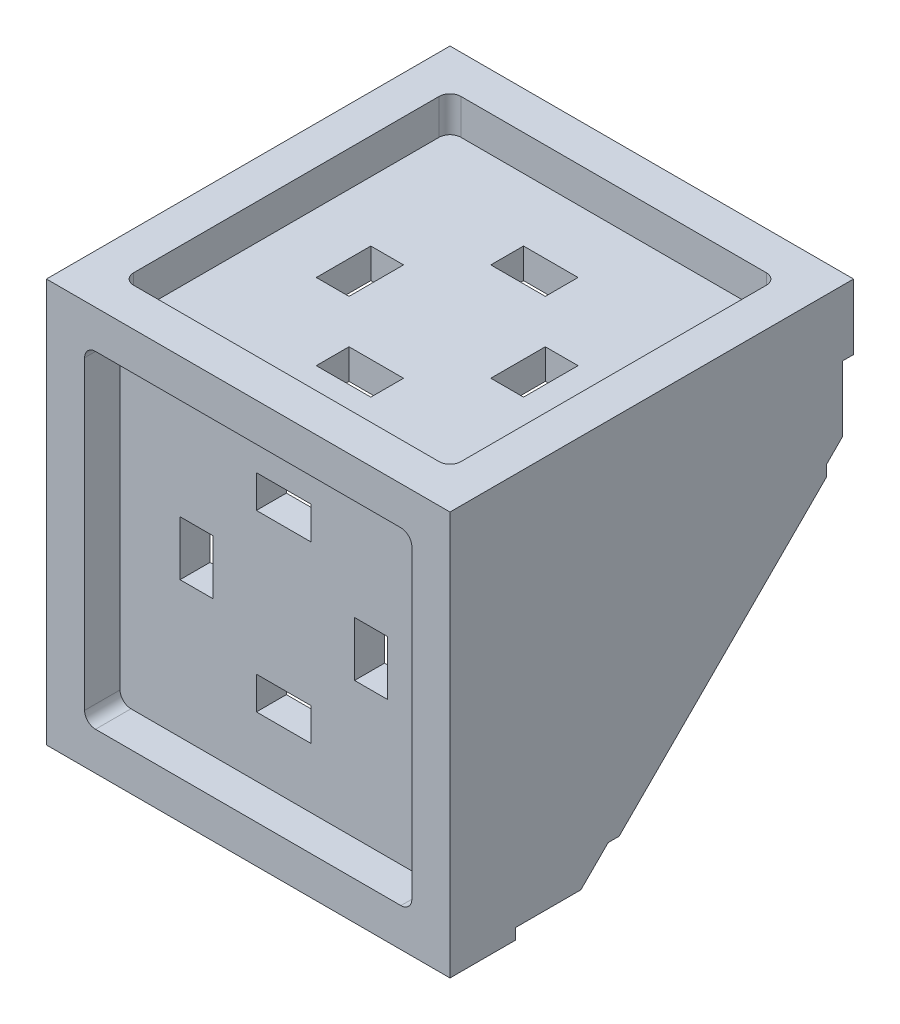
SolidWorks part; units mm, degrees
ref_plane "Front Plane" through (0, 0, 0) normal (0, 0, 1) x (1, 0, 0)
ref_plane "Top Plane" through (0, 0, 0) normal (0, 1, 0) x (1, 0, 0)
ref_plane "Right Plane" through (0, 0, 0) normal (1, 0, 0) x (0, 0, -1)
sketch "Sketch1" plane through (0, 0, 0) normal (0, 0, 1) x (1, 0, 0)
  line L0 (-9.398, 9.398) -> (-9.398, -9.398)
  line L1 (-9.398, -9.398) -> (9.398, -9.398)
  line L2 (9.398, -9.398) -> (9.398, 9.398)
  line L3 (9.398, 9.398) -> (-9.398, 9.398)
extrude "Boss-Extrude1" add sketch "Sketch1" against normal blind 3.048
ref_plane "Plane1" through (0, 9.398, 0) normal (0, 1, 0) x (1, 0, 0)
sketch "Sketch3" plane through (0, 9.398, 0) normal (0, 1, 0) x (1, 0, 0)
  line L0 (-9.398, 0) -> (-9.398, 18.796)
  line L1 (-9.398, 18.796) -> (9.398, 18.796)
  line L2 (9.398, 18.796) -> (9.398, 0)
  line L3 (9.398, 0) -> (-9.398, 0)
extrude "Boss-Extrude2" add sketch "Sketch3" against normal blind 3.048
sketch "Sketch4" plane through (0, 9.398, 0) normal (0, 1, 0) x (1, 0, 0)
  line L0 (-7.62, 1.778) -> (-7.62, 17.018)
  line L1 (-7.62, 17.018) -> (7.62, 17.018)
  line L2 (7.62, 17.018) -> (7.62, 1.778)
  line L3 (7.62, 1.778) -> (-7.62, 1.778)
extrude "Cut-Extrude1" cut sketch "Sketch4" against normal blind 1.651
sketch "Sketch5" plane through (0, 0, 0) normal (0, 0, 1) x (1, 0, 0)
  line L0 (-7.62, 7.62) -> (7.62, 7.62)
  line L1 (7.62, 7.62) -> (7.62, -7.62)
  line L2 (7.62, -7.62) -> (-7.62, -7.62)
  line L3 (-7.62, -7.62) -> (-7.62, 7.62)
extrude "Cut-Extrude2" cut sketch "Sketch5" against normal blind 1.651
sketch "Sketch6" plane through (0, 7.747, 0) normal (0, 1, 0) x (1, 0, 0)
  line L0 (-3.302, 7.9959) -> (-4.826, 7.9959)
  line L1 (-1.27, 14.0919) -> (1.27, 14.0919)
  line L2 (1.27, 14.0919) -> (1.27, 12.5679)
  line L3 (1.27, 12.5679) -> (-1.27, 12.5679)
  line L4 (-1.27, 12.5679) -> (-1.27, 14.0919)
  line L5 (-4.826, 7.9959) -> (-4.826, 10.5359)
  line L6 (-4.826, 10.5359) -> (-3.302, 10.5359)
  line L7 (-3.302, 10.5359) -> (-3.302, 7.9959)
  line L8 (1.27, 5.9639) -> (1.27, 4.4399)
  line L9 (1.27, 4.4399) -> (-1.27, 4.4399)
  line L10 (-1.27, 4.4399) -> (-1.27, 5.9639)
  line L11 (-1.27, 5.9639) -> (1.27, 5.9639)
  line L12 (3.302, 10.5359) -> (4.826, 10.5359)
  line L13 (4.826, 10.5359) -> (4.826, 7.9959)
  line L14 (4.826, 7.9959) -> (3.302, 7.9959)
  line L15 (3.302, 7.9959) -> (3.302, 10.5359)
  arc A0 (-3.8605, 7.9959) -> (-1.27, 5.4055) centre (0, 9.2659) ccw
  arc A1 (-1.27, 13.1264) -> (-3.8605, 10.5359) centre (0, 9.2659) ccw
  arc A2 (3.8605, 10.5359) -> (1.27, 13.1264) centre (0, 9.2659) ccw
  arc A3 (1.27, 5.4055) -> (3.8605, 7.9959) centre (0, 9.2659) ccw
  point P21 (0, 9.2659)
  dimension "D1" = 4
extrude "Cut-Extrude3" cut sketch "Sketch6" against normal blind 1.651 contours L11 L10 L9 L8 | L7 L6 L5 L0 | L15 L14 L13 L12 | L1 L2 L3 L4
sketch "Sketch7" plane through (0, 0, 0) normal (0, 0, 1) x (1, 0, 0)
  line L0 (-1.27, 4.826) -> (1.27, 4.826)
  line L1 (1.27, 4.826) -> (1.27, 3.302)
  line L2 (1.27, 3.302) -> (-1.27, 3.302)
  line L3 (-1.27, 3.302) -> (-1.27, 4.826)
  line L4 (3.302, 1.27) -> (4.826, 1.27)
  line L5 (4.826, 1.27) -> (4.826, -1.27)
  line L6 (4.826, -1.27) -> (3.302, -1.27)
  line L7 (3.302, -1.27) -> (3.302, 1.27)
  line L8 (1.27, -3.302) -> (1.27, -4.826)
  line L9 (1.27, -4.826) -> (-1.27, -4.826)
  line L10 (-1.27, -4.826) -> (-1.27, -3.302)
  line L11 (-1.27, -3.302) -> (1.27, -3.302)
  line L12 (-3.302, -1.27) -> (-4.826, -1.27)
  line L13 (-4.826, -1.27) -> (-4.826, 1.27)
  line L14 (-4.826, 1.27) -> (-3.302, 1.27)
  line L15 (-3.302, 1.27) -> (-3.302, -1.27)
  arc A0 (-3.8605, -1.27) -> (-1.27, -3.8605) centre (0, 0) ccw
  arc A1 (-1.27, 3.8605) -> (-3.8605, 1.27) centre (0, 0) ccw
  arc A2 (3.8605, 1.27) -> (1.27, 3.8605) centre (0, 0) ccw
  arc A3 (1.27, -3.8605) -> (3.8605, -1.27) centre (0, 0) ccw
  point P22 (0, 0)
  dimension "D1" = 4
extrude "Cut-Extrude4" cut sketch "Sketch7" against normal through all contours L3 L2 L1 L0 | L7 L6 L5 L4 | L11 L10 L9 L8 | L13 L14 L15 L12
ref_plane "Plane2" through (9.398, 0, 0) normal (1, 0, 0) x (0, 0, -1)
sketch "Sketch8" plane through (9.398, 0, 0) normal (1, 0, 0) x (0, 0, -1)
  line L0 (3.048, 6.35) -> (3.048, -8.89)
  line L1 (3.048, -9.398) -> (3.048, 6.35) construction
  line L2 (3.048, -8.89) -> (6.096, -8.89)
  line L3 (3.048, 6.35) -> (18.288, 6.35)
  line L4 (3.048, 6.35) -> (18.796, 6.35) construction
  line L5 (18.288, 6.35) -> (18.288, 3.302)
  line L6 (6.096, -8.89) -> (7.366, -7.62)
  line L7 (7.366, -7.62) -> (7.874, -7.62)
  line L8 (7.874, -7.62) -> (17.526, 2.032)
  line L9 (17.526, 2.54) -> (17.526, 2.032)
  line L10 (17.526, 2.54) -> (18.288, 3.302)
  dimension "D1" = 15.24
  dimension "D2" = 15.24
  dimension "D3" = 3.048
  dimension "D4" = 3.048
  dimension "D5" = 1.27
  dimension "D6" = 1.27
extrude "Boss-Extrude3" add sketch "Sketch8" against normal blind 1.651
fillet "Fillet1" radius 0.508 4 edges at (-7.62, 8.5725, -1.778) (7.62, 8.5725, -1.778) (7.62, 8.5725, -17.018) (-7.62, 8.5725, -17.018)
fillet "Fillet2" radius 0.508 4 edges at (-7.62, 7.62, -0.8255) (7.62, -7.62, -0.8255) (-7.62, -7.62, -0.8255) (7.62, 7.62, -0.8255)
